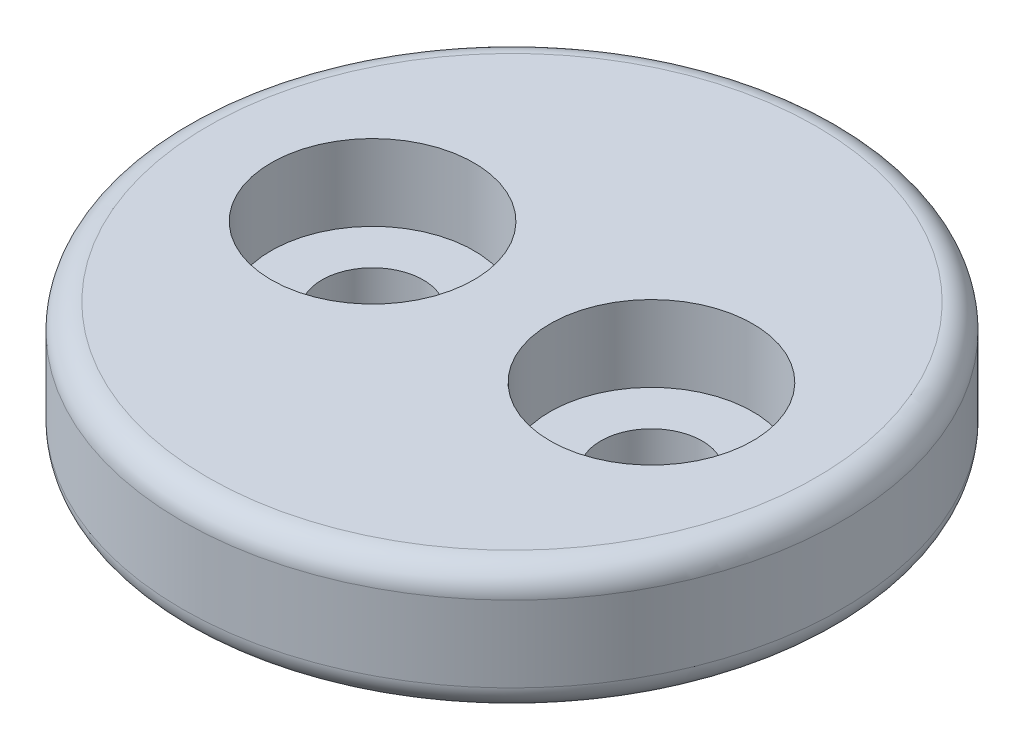
SolidWorks part; units mm, degrees
ref_plane "Front Plane" through (0, 0, 0) normal (0, 0, 1) x (1, 0, 0)
ref_plane "Top Plane" through (0, 0, 0) normal (0, 1, 0) x (1, 0, 0)
ref_plane "Right Plane" through (0, 0, 0) normal (1, 0, 0) x (0, 0, -1)
sketch "Sketch1" plane through (0, 0, 0) normal (0, 1, 0) x (1, 0, 0)
  line L0 (0, 0) -> (0, -16.51) construction
  circle A0 centre (0, 0) radius 16.51
  circle A2 centre (-6.985, 0) radius 2.54
  circle A3 centre (6.985, 0) radius 2.54
  dimension "D2" = 33.02
  dimension "D3" = 5.08
  dimension "D1" = 6.985
extrude "Boss-Extrude1" add sketch "Sketch1" along normal blind 6.35
sketch "Sketch2" plane through (0, 6.35, 0) normal (0, 1, 0) x (1, 0, 0)
  circle A0 centre (-6.985, 0) radius 5.08
  circle A1 centre (6.985, 0) radius 5.08
  dimension "D1" = 10.16
extrude "Cut-Extrude1" cut sketch "Sketch2" against normal blind 3.81 contours A0 | A1
fillet "Fillet1" radius 1.27 2 edges at (0, 0, 16.51) (0, 6.35, 16.51)
sketch "Sketch3" plane through (0, 6.35, 0) normal (0, 1, 0) x (1, 0, 0)
  circle A0 centre (0, 0) radius 1.905
  dimension "D1" = 3.81
extrude "Cut-Extrude4" [suppressed] cut sketch "Sketch3" against normal through all
